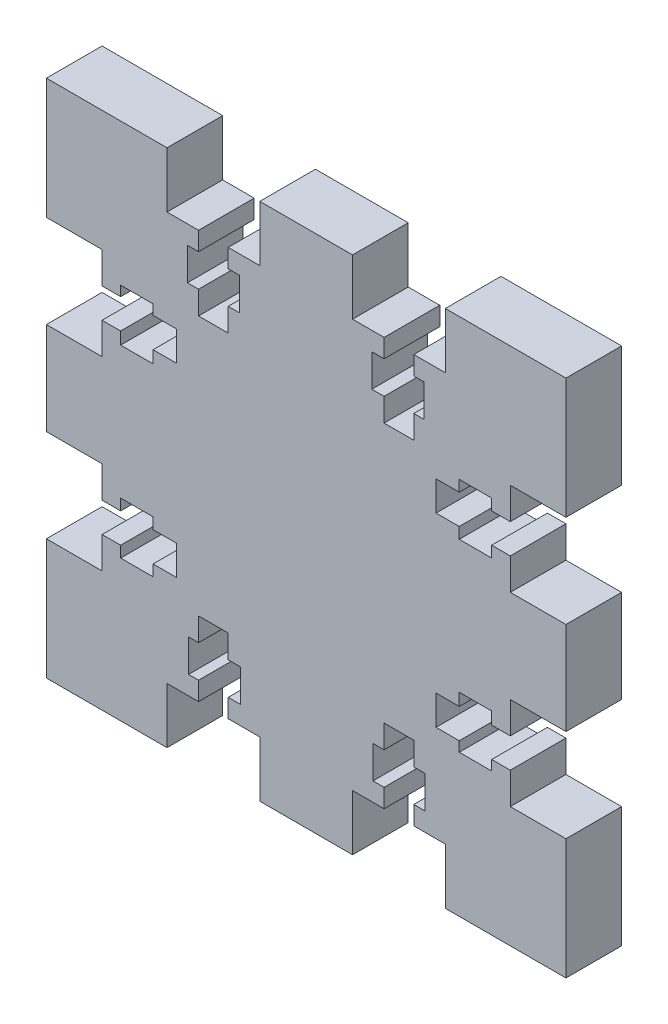
SolidWorks part; units mm, degrees
ref_plane "Plan de face" through (0, 0, 0) normal (0, 0, 1) x (1, 0, 0)
ref_plane "Plan de dessus" through (0, 0, 0) normal (0, 1, 0) x (1, 0, 0)
ref_plane "Plan de droite" through (0, 0, 0) normal (1, 0, 0) x (0, 0, -1)
sketch "Sketch1" plane through (0, 0, 0) normal (0, 0, 1) x (1, 0, 0)
  line L1 (-21.2669, 15.852) -> (34.7331, 15.852)
  line L2 (-21.2669, 15.852) -> (-21.2669, -40.148)
  line L3 (-21.2669, -40.148) -> (34.7331, -40.148)
  line L4 (34.7331, 15.852) -> (34.7331, -40.148)
  dimension "D1" = 56
  dimension "D2" = 56
extrude "Boss-Extrude1" add sketch "Sketch1" along normal blind 6
sketch "Sketch2" plane through (0, 0, 6) normal (0, 0, 1) x (1, 0, 0)
  line L0 (34.7331, 15.852) -> (-21.2669, 15.852) construction
  line L1 (-8.2669, 15.852) -> (1.7331, 15.852)
  line L2 (-8.2669, 15.852) -> (-8.2669, 9.852)
  line L3 (-8.2669, 9.852) -> (1.7331, 9.852)
  line L4 (1.7331, 15.852) -> (1.7331, 9.852)
  line L5 (-21.2669, 15.852) -> (-21.2669, -40.148) construction
  line L7 (11.7331, 15.852) -> (21.7331, 15.852)
  line L8 (11.7331, 15.852) -> (11.7331, 9.852)
  line L9 (11.7331, 9.852) -> (21.7331, 9.852)
  line L10 (21.7331, 15.852) -> (21.7331, 9.852)
  line L13 (28.7331, 2.852) -> (28.7331, -7.148)
  line L14 (34.7331, 2.852) -> (28.7331, 2.852)
  line L15 (34.7331, 2.852) -> (34.7331, -7.148)
  line L16 (34.7331, -7.148) -> (28.7331, -7.148)
  line L17 (34.7331, -17.148) -> (28.7331, -17.148)
  line L18 (34.7331, -17.148) -> (34.7331, -27.148)
  line L19 (34.7331, -27.148) -> (28.7331, -27.148)
  line L20 (28.7331, -17.148) -> (28.7331, -27.148)
  line L21 (21.7331, -34.148) -> (11.7331, -34.148)
  line L22 (21.7331, -40.148) -> (21.7331, -34.148)
  line L23 (21.7331, -40.148) -> (11.7331, -40.148)
  line L24 (11.7331, -40.148) -> (11.7331, -34.148)
  line L25 (1.7331, -40.148) -> (1.7331, -34.148)
  line L26 (1.7331, -40.148) -> (-8.2669, -40.148)
  line L27 (-8.2669, -40.148) -> (-8.2669, -34.148)
  line L28 (1.7331, -34.148) -> (-8.2669, -34.148)
  line L29 (-15.2669, -27.148) -> (-15.2669, -17.148)
  line L30 (-21.2669, -27.148) -> (-15.2669, -27.148)
  line L31 (-21.2669, -27.148) -> (-21.2669, -17.148)
  line L32 (-21.2669, -17.148) -> (-15.2669, -17.148)
  line L33 (-21.2669, -7.148) -> (-15.2669, -7.148)
  line L34 (-21.2669, -7.148) -> (-21.2669, 2.852)
  line L35 (-21.2669, 2.852) -> (-15.2669, 2.852)
  line L36 (-15.2669, -7.148) -> (-15.2669, 2.852)
  point P12 (1.7331, 12.852)
  point P17 (6.7331, -12.148)
  dimension "D1" = 13
  dimension "D2" = 10
  dimension "D3" = 10
  dimension "D4" = 10
  dimension "D6" = 6
  dimension "D5" = 6
  dimension "D7" = 4
extrude "Cut-Extrude1" cut sketch "Sketch2" against normal through all
sketch "Sketch4" plane through (0, 9.852, 0) normal (0, 1, 0) x (1, 0, 0)
  line L0 (-8.2669, -6) -> (1.7331, -6) construction
  line L1 (-8.2669, 0) -> (1.7331, 0) construction
  line L2 (11.7331, -6) -> (21.7331, -6) construction
  line L3 (11.7331, 0) -> (21.7331, 0) construction
  line L4 (18.3331, -6) -> (15.1331, -6)
  line L5 (18.3331, -6) -> (18.3331, 0)
  line L6 (18.3331, 0) -> (15.1331, 0)
  line L7 (15.1331, -6) -> (15.1331, 0)
  line L8 (18.3331, -6) -> (15.1331, 0) construction
  line L9 (18.3331, 0) -> (15.1331, -6) construction
  line L11 (-1.6669, -6) -> (-4.8669, -6)
  line L12 (-1.6669, -6) -> (-1.6669, 0)
  line L13 (-1.6669, 0) -> (-4.8669, 0)
  line L14 (-4.8669, -6) -> (-4.8669, 0)
  line L15 (-1.6669, -6) -> (-4.8669, 0) construction
  line L16 (-1.6669, 0) -> (-4.8669, -6) construction
  line L18 (21.7331, 0) -> (21.7331, -6) construction
  point P0 (0, 0)
  point P7 (-3.2669, 0)
  point P9 (16.7331, -3)
  point P16 (-3.2669, -3)
  dimension "D1" = 3.2
  dimension "D2" = 3.2
  dimension "D3" = 3.4
extrude "Cut-Extrude2" cut sketch "Sketch4" against normal blind 8
sketch "Sketch10" plane through (28.7331, 0, 0) normal (1, 0, 0) x (0, 0, -1)
  line L0 (-6, 2.852) -> (-6, -7.148) construction
  line L7 (-6, -0.548) -> (0, -0.548)
  line L8 (-6, -0.548) -> (-6, -3.748)
  line L9 (-6, -3.748) -> (0, -3.748)
  line L10 (0, -0.548) -> (0, -3.748)
  line L11 (0, 2.852) -> (0, -7.148) construction
  line L12 (0, 2.852) -> (-6, 2.852) construction
  line L13 (-6, -17.148) -> (-6, -27.148) construction
  line L14 (-6, -20.548) -> (0, -20.548)
  line L15 (-6, -20.548) -> (-6, -23.748)
  line L16 (-6, -23.748) -> (0, -23.748)
  line L17 (0, -20.548) -> (0, -23.748)
  line L18 (0, -17.148) -> (0, -27.148) construction
  line L19 (0, -17.148) -> (-6, -17.148) construction
  dimension "D1" = 3.2
  dimension "D2" = 3.4
  dimension "D3" = 3.2
  dimension "D4" = 3.4
extrude "Cut-Extrude7" cut sketch "Sketch10" against normal blind 8
sketch "Sketch11" plane through (0, -34.148, 0) normal (0, -1, 0) x (1, 0, 0)
  line L0 (21.7331, 6) -> (11.7331, 6) construction
  line L1 (15.1331, 6) -> (18.3331, 6)
  line L2 (15.1331, 6) -> (15.1331, 0)
  line L3 (15.1331, 0) -> (18.3331, 0)
  line L4 (18.3331, 6) -> (18.3331, 0)
  line L5 (21.7331, 0) -> (11.7331, 0) construction
  line L6 (11.7331, 0) -> (11.7331, 6) construction
  line L7 (1.7331, 6) -> (-8.2669, 6) construction
  line L8 (-4.8669, 6) -> (-1.6669, 6)
  line L9 (-4.8669, 6) -> (-4.8669, 0)
  line L10 (-4.8669, 0) -> (-1.6669, 0)
  line L11 (-1.6669, 6) -> (-1.6669, 0)
  line L12 (1.7331, 0) -> (-8.2669, 0) construction
  line L13 (1.7331, 0) -> (1.7331, 6) construction
  point P20 (1.7331, 3)
  dimension "D1" = 3.2
  dimension "D2" = 3.4
  dimension "D3" = 3.2
  dimension "D4" = 3.4
extrude "Cut-Extrude8" cut sketch "Sketch11" against normal blind 8
sketch "Sketch12" plane through (-15.2669, 0, 0) normal (-1, 0, 0) x (0, 0, 1)
  line L0 (6, -7.148) -> (6, 2.852) construction
  line L1 (6, -0.548) -> (0, -0.548)
  line L2 (6, -0.548) -> (6, -3.748)
  line L3 (6, -3.748) -> (0, -3.748)
  line L4 (0, -0.548) -> (0, -3.748)
  line L5 (0, -7.148) -> (0, 2.852) construction
  line L6 (0, 2.852) -> (6, 2.852) construction
  line L7 (0, -27.148) -> (0, -17.148) construction
  line L8 (0, -20.548) -> (6, -20.548)
  line L9 (0, -20.548) -> (0, -23.748)
  line L10 (0, -23.748) -> (6, -23.748)
  line L11 (6, -20.548) -> (6, -23.748)
  line L12 (6, -27.148) -> (6, -17.148) construction
  line L13 (0, -17.148) -> (6, -17.148) construction
  point P10 (3, 2.852)
  dimension "D1" = 3.4
  dimension "D2" = 3.2
  dimension "D3" = 3.4
  dimension "D4" = 3.2
extrude "Cut-Extrude9" cut sketch "Sketch12" against normal blind 8
sketch "Sketch13" plane through (0, 0, 0) normal (0, 0, -1) x (-1, 0, 0)
  line L0 (-28.7331, -17.148) -> (-28.7331, -20.548) construction
  line L1 (-20.7331, -3.748) -> (-20.7331, -0.548) construction
  line L2 (-28.7331, 2.852) -> (-28.7331, -0.548) construction
  line L3 (-26.7331, -24.826) -> (-23.2331, -24.826)
  line L4 (-26.7331, -24.826) -> (-26.7331, -19.226)
  line L5 (-26.7331, -19.226) -> (-23.2331, -19.226)
  line L6 (-23.2331, -24.826) -> (-23.2331, -19.226)
  line L7 (-19.411, 7.852) -> (-13.811, 7.852)
  line L8 (-26.7331, -4.948) -> (-23.2331, -4.948)
  line L9 (-26.7331, -4.948) -> (-26.7331, 0.652)
  line L10 (-26.7331, 0.652) -> (-23.2331, 0.652)
  line L11 (-23.2331, -4.948) -> (-23.2331, 0.652)
  line L12 (-19.411, 7.852) -> (-19.411, 4.352)
  line L13 (-19.411, 4.352) -> (-13.811, 4.352)
  line L14 (-13.811, 7.852) -> (-13.811, 4.352)
  line L15 (0.4669, 7.852) -> (6.0669, 7.852)
  line L16 (0.4669, 7.852) -> (0.4669, 4.352)
  line L17 (0.4669, 4.352) -> (6.0669, 4.352)
  line L18 (6.0669, 7.852) -> (6.0669, 4.352)
  line L19 (13.2669, 0.5299) -> (13.2669, -5.0701)
  line L20 (13.2669, 0.5299) -> (9.7669, 0.5299)
  line L21 (9.7669, 0.5299) -> (9.7669, -5.0701)
  line L22 (13.2669, -5.0701) -> (9.7669, -5.0701)
  line L23 (13.2669, -19.348) -> (13.2669, -24.948)
  line L24 (13.2669, -19.348) -> (9.7669, -19.348)
  line L25 (9.7669, -19.348) -> (9.7669, -24.948)
  line L26 (13.2669, -24.948) -> (9.7669, -24.948)
  line L27 (5.9448, -32.148) -> (0.3448, -32.148)
  line L28 (5.9448, -32.148) -> (5.9448, -28.648)
  line L29 (5.9448, -28.648) -> (0.3448, -28.648)
  line L30 (0.3448, -32.148) -> (0.3448, -28.648)
  line L31 (-13.9331, -32.148) -> (-19.5331, -32.148)
  line L32 (-13.9331, -32.148) -> (-13.9331, -28.648)
  line L33 (-13.9331, -28.648) -> (-19.5331, -28.648)
  line L34 (-19.5331, -32.148) -> (-19.5331, -28.648)
  point P6 (-6.7331, -12.148)
  point P7 (-28.7331, -18.848)
  point P12 (-26.7331, -2.148)
  point P15 (-20.7331, -2.148)
  dimension "D1" = 5.6
  dimension "D2" = 3.5
  dimension "D3" = 2
  dimension "D4" = 5.6
  dimension "D5" = 3.5
  dimension "D6" = 2
  dimension "D7" = 4
extrude "Cut-Extrude10" cut sketch "Sketch13" against normal through all
